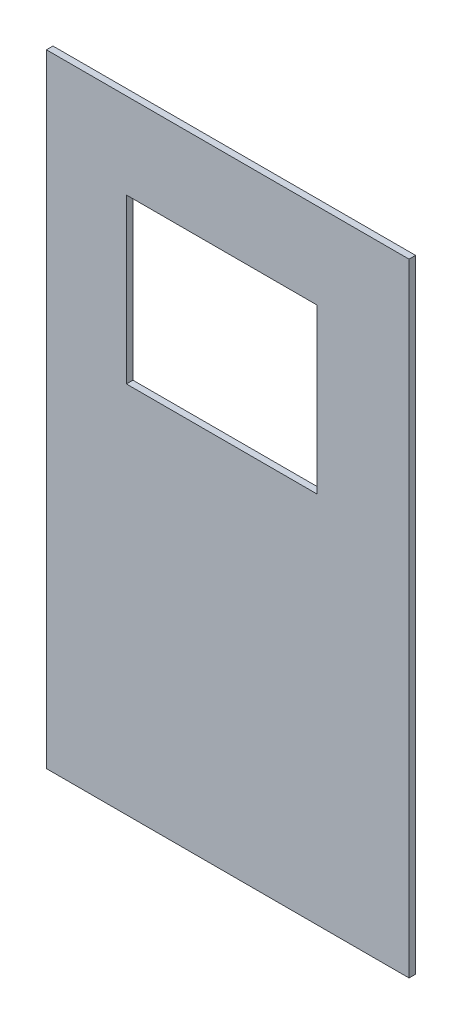
SolidWorks part; units mm, degrees
ref_plane "Plan de face" through (0, 0, 0) normal (0, 0, 1) x (1, 0, 0)
ref_plane "Plan de dessus" through (0, 0, 0) normal (0, 1, 0) x (1, 0, 0)
ref_plane "Plan de droite" through (0, 0, 0) normal (1, 0, 0) x (0, 0, -1)
sketch "Esquisse1" plane through (0, 0, 0) normal (0, 0, 1) x (1, 0, 0)
  line L1 (-161.8321, 173.5369) -> (71.1679, 173.5369)
  line L2 (-161.8321, 173.5369) -> (-161.8321, -226.4631)
  line L3 (-161.8321, -226.4631) -> (71.1679, -226.4631)
  line L4 (71.1679, 173.5369) -> (71.1679, -226.4631)
  dimension "D1" = 400
  dimension "D2" = 233
extrude "Boss.-Extru.1" add sketch "Esquisse1" along normal blind 4.2
sketch "Esquisse2" plane through (0, 0, 4.2) normal (0, 0, 1) x (1, 0, 0)
  line L1 (-110.458, 118.4398) -> (11.8657, 118.4398)
  line L2 (-110.458, 118.4398) -> (-110.458, 13.2802)
  line L3 (-110.458, 13.2802) -> (11.8657, 13.2802)
  line L4 (11.8657, 118.4398) -> (11.8657, 13.2802)
extrude "Enlèv. mat.-Extru.1" cut sketch "Esquisse2" against normal through all and the other way through all
